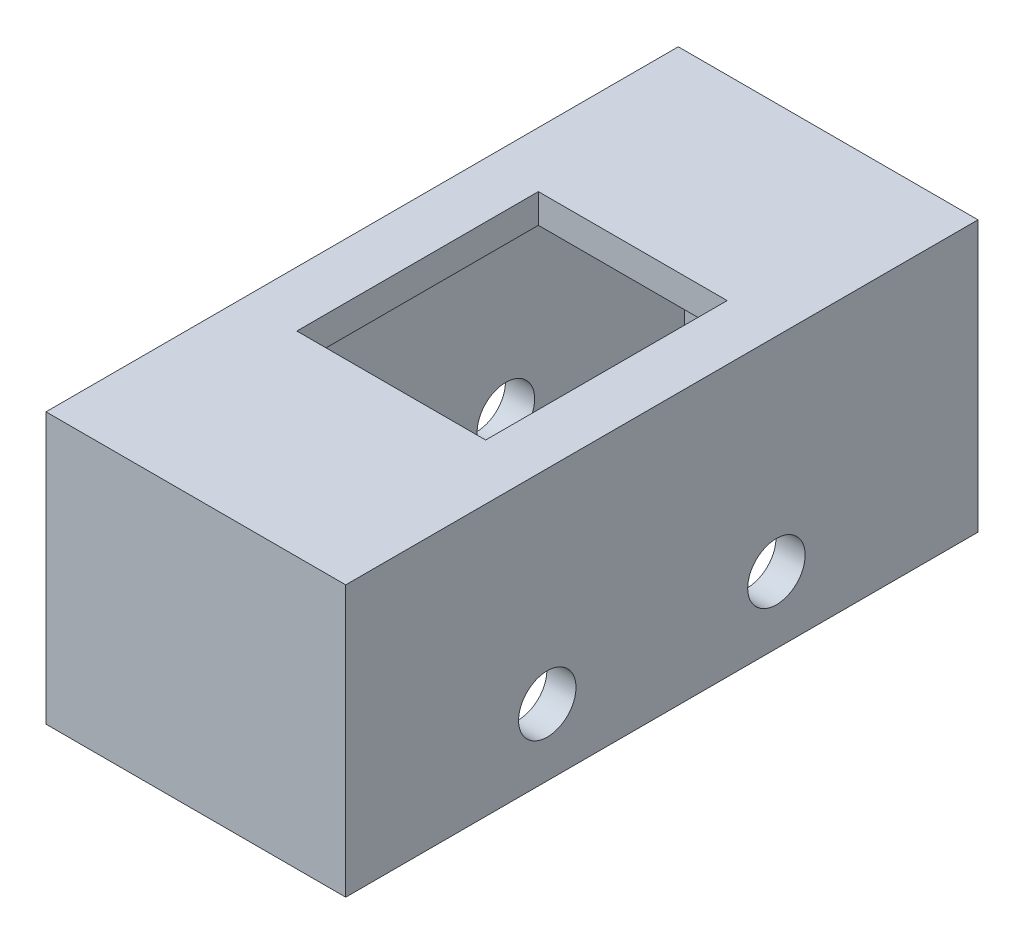
SolidWorks part; units mm, degrees
ref_plane "Front Plane" through (0, 0, 0) normal (0, 0, 1) x (1, 0, 0)
ref_plane "Top Plane" through (0, 0, 0) normal (0, 1, 0) x (1, 0, 0)
ref_plane "Right Plane" through (0, 0, 0) normal (1, 0, 0) x (0, 0, -1)
sketch "Sketch1" plane through (0, 0, 0) normal (0, 1, 0) x (1, 0, 0)
  line L1 (-13.04, -27.5084) -> (13.04, -27.5084)
  line L2 (-13.04, -27.5084) -> (-13.04, 27.5084)
  line L3 (-13.04, 27.5084) -> (13.04, 27.5084)
  line L4 (13.04, -27.5084) -> (13.04, 27.5084)
  line L5 (-13.04, -27.5084) -> (13.04, 27.5084) construction
  line L6 (-13.04, 27.5084) -> (13.04, -27.5084) construction
  line L7 (-10.5, 25.5) -> (10.5, 25.5)
  line L8 (-10.5, 25.5) -> (-10.5, -25.5)
  line L9 (-10.5, -25.5) -> (10.5, -25.5)
  line L10 (10.5, 25.5) -> (10.5, -25.5)
  line L11 (-10.5, 25.5) -> (10.5, -25.5) construction
  line L12 (-10.5, -25.5) -> (10.5, 25.5) construction
  point P0 (0, 0)
  point P6 (0, 0)
  dimension "D1" = 2.54
  dimension "D2" = 2.0084
  dimension "D3" = 21
  dimension "D4" = 51
extrude "Boss-Extrude1" add sketch "Sketch1" along normal blind 21
sketch "Sketch3" plane through (0, 0, 27.5084) normal (0, 0, 1) x (1, 0, 0)
  line L0 (13.04, 21) -> (13.04, 0) construction
  line L1 (-13.04, 21) -> (13.04, 21)
  line L2 (-13.04, 21) -> (-13.04, 23.54)
  line L3 (-13.04, 23.54) -> (13.04, 23.54)
  line L4 (13.04, 21) -> (13.04, 23.54)
  dimension "D1" = 2.54
extrude "Boss-Extrude2" add sketch "Sketch3" against normal through all
sketch "Sketch4" plane through (0, 23.54, 0) normal (0, 1, 0) x (1, 0, 0)
  line L0 (13.04, -27.5084) -> (-13.04, -27.5084) construction
  line L1 (-8.214, 10.5084) -> (8.214, 10.5084)
  line L2 (-8.214, 10.5084) -> (-8.214, -10.5084)
  line L3 (-8.214, -10.5084) -> (8.214, -10.5084)
  line L4 (8.214, 10.5084) -> (8.214, -10.5084)
  line L5 (13.04, 27.5084) -> (-13.04, 27.5084) construction
  line L6 (-13.04, 27.5084) -> (-13.04, -27.5084) construction
  line L7 (13.04, 27.5084) -> (13.04, -27.5084) construction
  dimension "D1" = 17
  dimension "D2" = 17
  dimension "D3" = 4.826
  dimension "D4" = 4.826
extrude "Cut-Extrude1" cut sketch "Sketch4" against normal up to next
sketch "Sketch5" plane through (0, 0, 0) normal (1, 0, 0) x (0, 0, -1)
  line L0 (-9.9684, 29.056) -> (-9.9684, -9.7597) construction
  line L1 (9.9684, 29.056) -> (9.9684, -9.7597) construction
  line L2 (-27.5084, 23.54) -> (-27.5084, 0) construction
  line L3 (27.5084, 23.54) -> (27.5084, 0) construction
  line L4 (-29.9887, 21) -> (34.7417, 21) construction
  line L5 (27.5084, 23.54) -> (-27.5084, 23.54) construction
  line L6 (-29.9887, 5.8) -> (34.7417, 5.8) construction
  circle A0 centre (-9.9684, 5.8) radius 2.5
  circle A1 centre (9.9684, 5.8) radius 2.5
  dimension "D5" = 5
  dimension "D6" = 5
  dimension "D1" = 17.54
  dimension "D2" = 17.54
  dimension "D3" = 2.54
  dimension "D4" = 17.74
extrude "Cut-Extrude2" cut sketch "Sketch5" against normal up to next and the other way up to next
